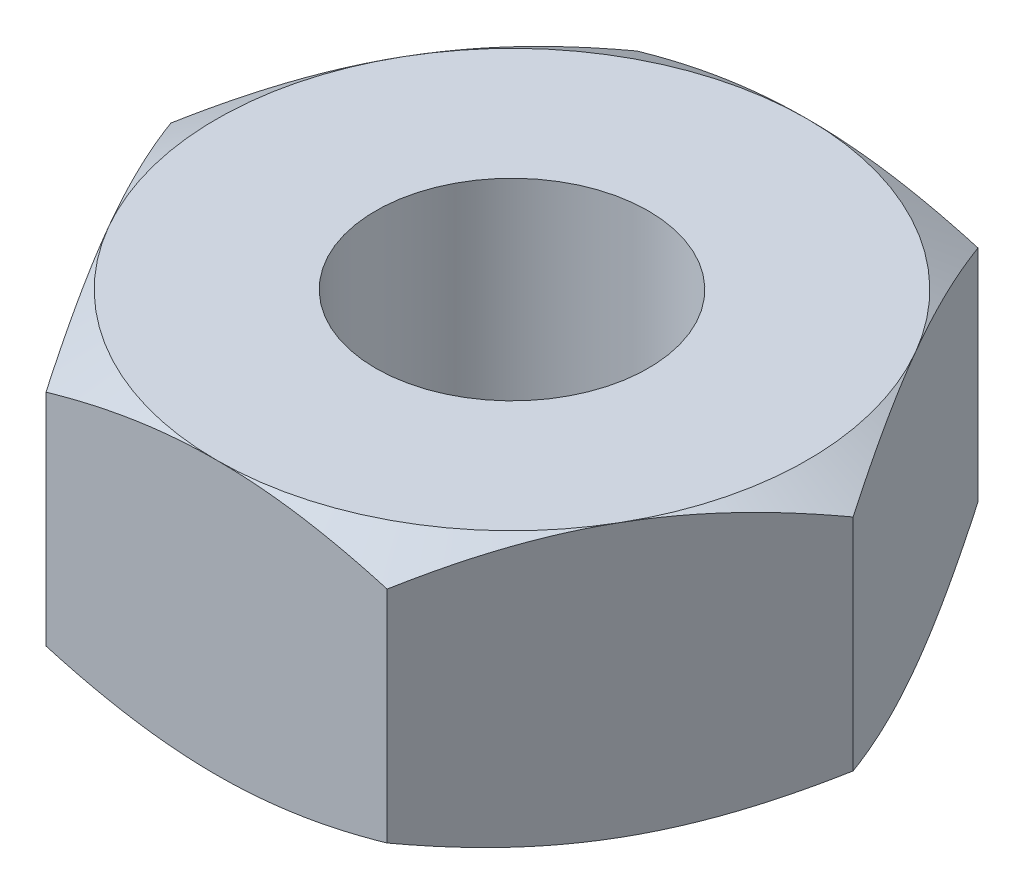
SolidWorks part; units mm, degrees
ref_plane "Front Plane" through (0, 0, 0) normal (0, 0, 1) x (1, 0, 0)
ref_plane "Top Plane" through (0, 0, 0) normal (0, 1, 0) x (1, 0, 0)
ref_plane "Right Plane" through (0, 0, 0) normal (1, 0, 0) x (0, 0, -1)
sketch "Sketch1" plane through (0, 0, 0) normal (0, 1, 0) x (1, 0, 0)
  line L1 (7.5056, -13) -> (15.0111, 0)
  line L2 (15.0111, 0) -> (7.5056, 13)
  line L3 (7.5056, 13) -> (-7.5056, 13)
  line L4 (-7.5056, 13) -> (-15.0111, 0)
  line L5 (-15.0111, 0) -> (-7.5056, -13)
  line L6 (-7.5056, -13) -> (7.5056, -13)
  circle A0 centre (0, 0) radius 13 construction
  circle A1 centre (0, 0) radius 6
  point P11 (0, -13)
  dimension "D1" = 26
  dimension "D2" = 12
extrude "Boss-Extrude1" add sketch "Sketch1" along normal mid plane 12
sketch "Sketch2" plane through (0, 6, 0) normal (0, 1, 0) x (1, 0, 0)
  line L0 (-7.5056, -13) -> (7.5056, -13) construction
  circle A0 centre (0, 0) radius 13
extrude "Cut-Extrude1" cut sketch "Sketch2" against normal blind 5 draft 60 flip side to cut
mirror "Mirror1" about plane through (0, 0, 0) normal (0, 1, 0) of "Cut-Extrude1"
